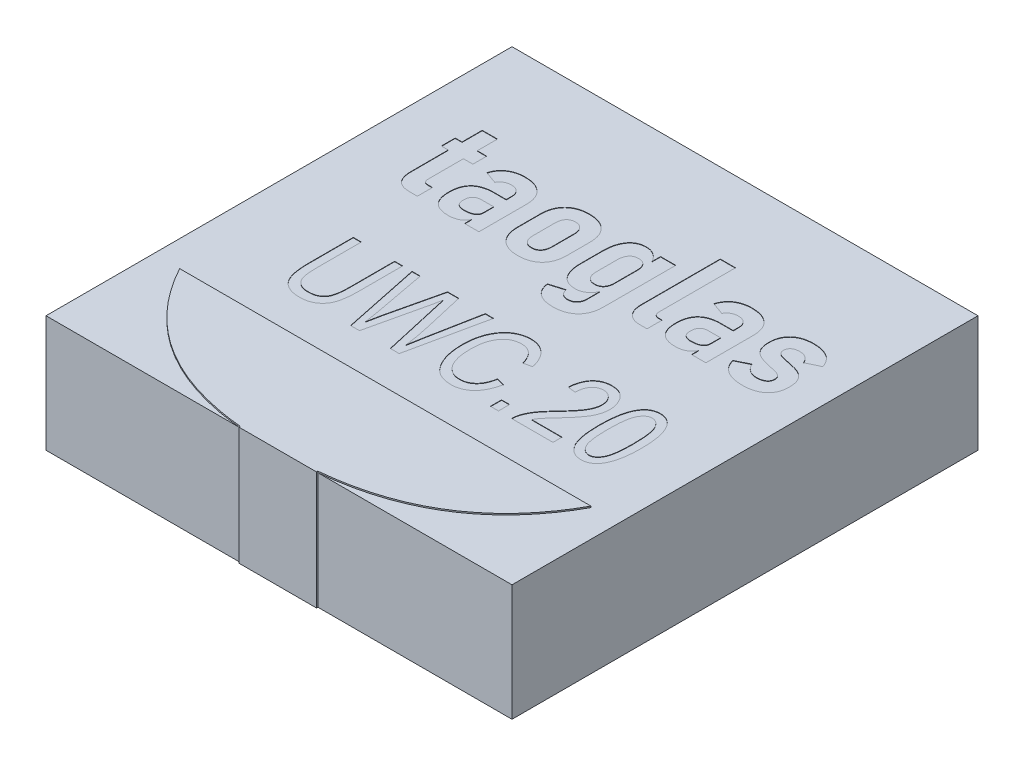
SolidWorks part; units mm, degrees
ref_plane "Front Plane" through (0, 0, 0) normal (0, 0, 1) x (1, 0, 0)
ref_plane "Top Plane" through (0, 0, 0) normal (0, 1, 0) x (1, 0, 0)
ref_plane "Right Plane" through (0, 0, 0) normal (1, 0, 0) x (0, 0, -1)
sketch "Sketch1" plane through (0, 0, 0) normal (0, 1, 0) x (1, 0, 0)
  line L1 (-6, -6) -> (6, -6)
  line L2 (-6, -6) -> (-6, 6)
  line L3 (-6, 6) -> (6, 6)
  line L4 (6, -6) -> (6, 6)
  line L5 (-6, -6) -> (6, 6) construction
  line L6 (-6, 6) -> (6, -6) construction
  point P0 (0, 0)
  dimension "D1" = 12
extrude "Boss-Extrude1" add sketch "Sketch1" along normal blind 3 contours L2 L3 L4 L1
sketch "Sketch2" plane through (0, 3, 0) normal (0, 1, 0) x (1, 0, 0)
  text T0 "taoglas" font "Bahnschrift SemiBold SemiConden" height 2.5
sketch "Sketch3" plane through (0, 3, 0) normal (0, 1, 0) x (1, 0, 0)
  text T0 "UWC.20" font "Arial Narrow" height 2
extrude "Cut-Extrude1" cut sketch "Sketch2" against normal blind 0.01
extrude "Cut-Extrude2" cut sketch "Sketch3" against normal blind 0.01
sketch "Sketch4" plane through (0, 3, 0) normal (0, 1, 0) x (1, 0, 0)
  line L0 (-1, -6) -> (1, -6)
  line L1 (-6, -6) -> (6, -6) construction
  line L2 (5.2952, -3.2631) -> (-5.2952, -3.2631)
  line L3 (-6, -6) -> (-6, 6) construction
  line L4 (6, -6) -> (6, 6) construction
  spline S0 degree 2 poles (1, -6) (3.9642, -5.7157) (5.2952, -3.2631) knots 0 0 0 1 1 1
  spline S1 degree 2 poles (-1, -6) (-3.9642, -5.7157) (-5.2952, -3.2631) knots 0 0 0 1 1 1
  point P4 (0, -6)
  point P5 (0, -6)
  point P9 (0, 0)
  point P12 (0, 0)
  point P15 (-5.4538, -4.6894)
  dimension "D1" = 2
  dimension "D2" = 5.2952
  dimension "D3" = 1.2741
  dimension "D4" = 1.8496
  dimension "D5" = 2.7369
  dimension "D6" = 1.2741
  dimension "D7" = 1.8496
  dimension "D8" = 0.7048
extrude "Boss-Extrude2" add sketch "Sketch4" along normal blind 0.035
sketch "Sketch5" plane through (0, 0, 6) normal (0, 0, 1) x (1, 0, 0)
  line L0 (-6, 0) -> (6, 0) construction
  line L1 (1, 3.035) -> (-1, 3.035)
  line L2 (1, 3.035) -> (1, 0)
  line L3 (1, 0) -> (-1, 0)
  line L4 (-1, 3.035) -> (-1, 0)
  point P7 (0, 0)
extrude "Boss-Extrude3" add sketch "Sketch5" along normal blind 0.035
sketch "Sketch6" plane through (0, 0, 0) normal (0, -1, 0) x (-1, 0, 0)
  line L0 (-6, -6) -> (-6, 6) construction
  line L1 (-5.9, 5.9) -> (-4.1, 5.9)
  line L2 (-5.9, 5.9) -> (-5.9, 4.1)
  line L3 (-5.9, 4.1) -> (-4.1, 4.1)
  line L4 (-4.1, 5.9) -> (-4.1, 4.1)
  line L5 (6, 6) -> (-6, 6) construction
  line L6 (0, 18.5872) -> (0, -6.7872) construction
  line L7 (7.1901, 0) -> (-6.6121, 0) construction
  line L8 (-0.9, 5.9) -> (0.9, 5.9)
  line L9 (-0.9, 5.9) -> (-0.9, 4.1)
  line L10 (-0.9, 4.1) -> (0.9, 4.1)
  line L11 (0.9, 5.9) -> (0.9, 4.1)
  line L12 (5.9, 4.1) -> (4.1, 4.1)
  line L13 (4.1, 5.9) -> (4.1, 4.1)
  line L14 (5.9, 5.9) -> (4.1, 5.9)
  line L15 (5.9, 5.9) -> (5.9, 4.1)
  line L16 (-0.9, -5.9) -> (-0.9, -4.1)
  line L17 (-0.9, -4.1) -> (0.9, -4.1)
  line L18 (0.9, -5.9) -> (0.9, -4.1)
  line L19 (-0.9, -5.9) -> (0.9, -5.9)
  line L20 (-5.9, -4.1) -> (-4.1, -4.1)
  line L21 (-4.1, -5.9) -> (-4.1, -4.1)
  line L22 (-5.9, -5.9) -> (-4.1, -5.9)
  line L23 (-5.9, -5.9) -> (-5.9, -4.1)
  line L24 (5.9, -5.9) -> (5.9, -4.1)
  line L25 (5.9, -5.9) -> (4.1, -5.9)
  line L26 (4.1, -5.9) -> (4.1, -4.1)
  line L27 (5.9, -4.1) -> (4.1, -4.1)
  point P17 (0.867, 4.9306)
  point P18 (-0.4642, 1.2524)
  point P19 (0, 5.9)
  dimension "D1" = 1.8
  dimension "D2" = 0.1
  dimension "D3" = 0.1
extrude "Boss-Extrude4" add sketch "Sketch6" along normal blind 0.035
